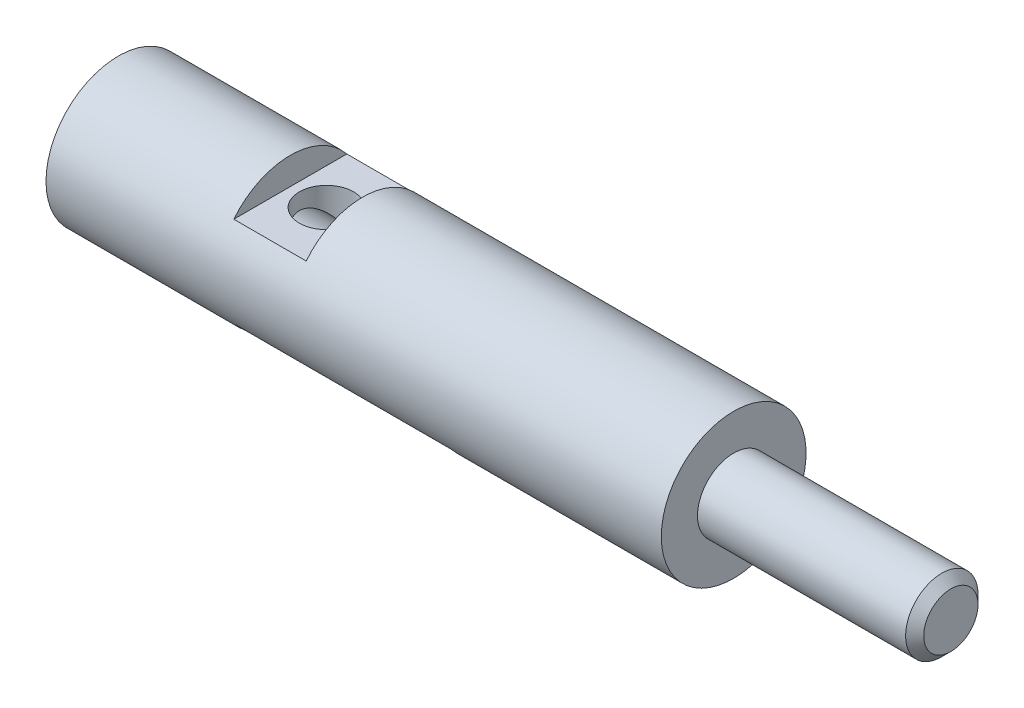
SolidWorks part; units mm, degrees
ref_plane "Front Plane" through (0, 0, 0) normal (0, 0, 1) x (1, 0, 0)
ref_plane "Top Plane" through (0, 0, 0) normal (0, 1, 0) x (1, 0, 0)
ref_plane "Right Plane" through (0, 0, 0) normal (1, 0, 0) x (0, 0, -1)
sketch "Sketch1" plane through (0, 0, 0) normal (0, 0, 1) x (1, 0, 0)
  line L0 (-21.4194, 0) -> (24.129, 0) construction
  line L1 (-15.6774, 0) -> (-15.6774, -4)
  line L2 (-15.6774, -4) -> (18.3226, -4)
  line L7 (18.3226, -4) -> (18.3226, -2)
  line L8 (18.3226, -2) -> (30.3226, -2)
  line L9 (30.3226, -2) -> (30.3226, 0)
  line L10 (30.3226, 0) -> (-15.6774, 0)
  dimension "D1" = 4
  dimension "D4" = 34
  dimension "D5" = 12
  dimension "D6" = 2
revolve "Revolve1" add sketch "Sketch1" angle 360 about L0
chamfer "Chamfer1" distance 0.5 angle 45 1 edges at (30.3226, 0, 2)
hole_wizard "Ø3.2 (3.2) Diameter Hole1" positions "Sketch2" profile "Sketch3" hole size "Ø3.2" standard "DIN"
sketch "Sketch2" plane through (-15.6774, 0, 0) normal (-1, 0, 0) x (0, 0, 1)
  point P0 (0, 0)
sketch "Sketch3" plane through (-15.6774, 0, 0) normal (0, 1, 0) x (0, 0, 1)
  line L0 (0, 0) -> (0, 14.9614)
  line L1 (0, 14.9614) -> (1.6, 14)
  line L2 (1.6, 14) -> (1.6, 0)
  line L5 (1.6, 0) -> (0, 0)
  line L10 (0, 14.9614) -> (-1.6, 14) construction
  line L11 (0, -6.35) -> (0, 107.95) construction
  dimension "Hole Dia." = 3.2
  dimension "Hole Depth" = 14
  dimension "Drill Angle" = 118
sketch "Sketch4" plane through (0, 0, 0) normal (0, 0, 1) x (1, 0, 0)
  line L0 (-15.6774, -4) -> (18.3226, -4) construction
  line L1 (-6.1774, -4) -> (5.8226, -4)
  line L2 (-6.1774, -4) -> (-6.1774, -2.5)
  line L3 (-6.1774, -2.5) -> (5.8226, -2.5)
  line L4 (5.8226, -4) -> (5.8226, -2.5)
  line L5 (18.3226, 4) -> (-15.6774, 4) construction
  line L6 (-6.1774, 4) -> (-2.1774, 4)
  line L7 (-6.1774, 4) -> (-6.1774, 2.5)
  line L8 (-6.1774, 2.5) -> (-2.1774, 2.5)
  line L9 (-2.1774, 4) -> (-2.1774, 2.5)
  line L10 (-15.6774, 4) -> (-15.6774, -4) construction
  dimension "D1" = 12
  dimension "D2" = 1.5
  dimension "D3" = 1.5
  dimension "D4" = 4
  dimension "D5" = 9.5
extrude "Cut-Extrude1" cut sketch "Sketch4" against normal through all both and the other way through all
hole_wizard "Ø3.0 (3) Diameter Hole1" positions "Sketch7" profile "Sketch6" hole size "Ø3.0" standard "DIN"
sketch "Sketch7" plane through (0, 2.5, 0) normal (0, 1, 0) x (1, 0, 0)
  point P0 (-4.1774, 0)
sketch "Sketch6" plane through (-4.1774, 2.5, 0) normal (1, 0, 0) x (0, 0, 1)
  line L0 (0, 0) -> (0, 0.9)
  line L1 (0, 0.9) -> (1.5, 0.9)
  line L2 (1.5, 0.9) -> (1.5, 0)
  line L5 (1.5, 0) -> (0, 0)
  line L11 (0, -6.35) -> (0, 107.95) construction
  dimension "Thru Hole Dia." = 3
  dimension "Thru Hole Depth" = 0.9
